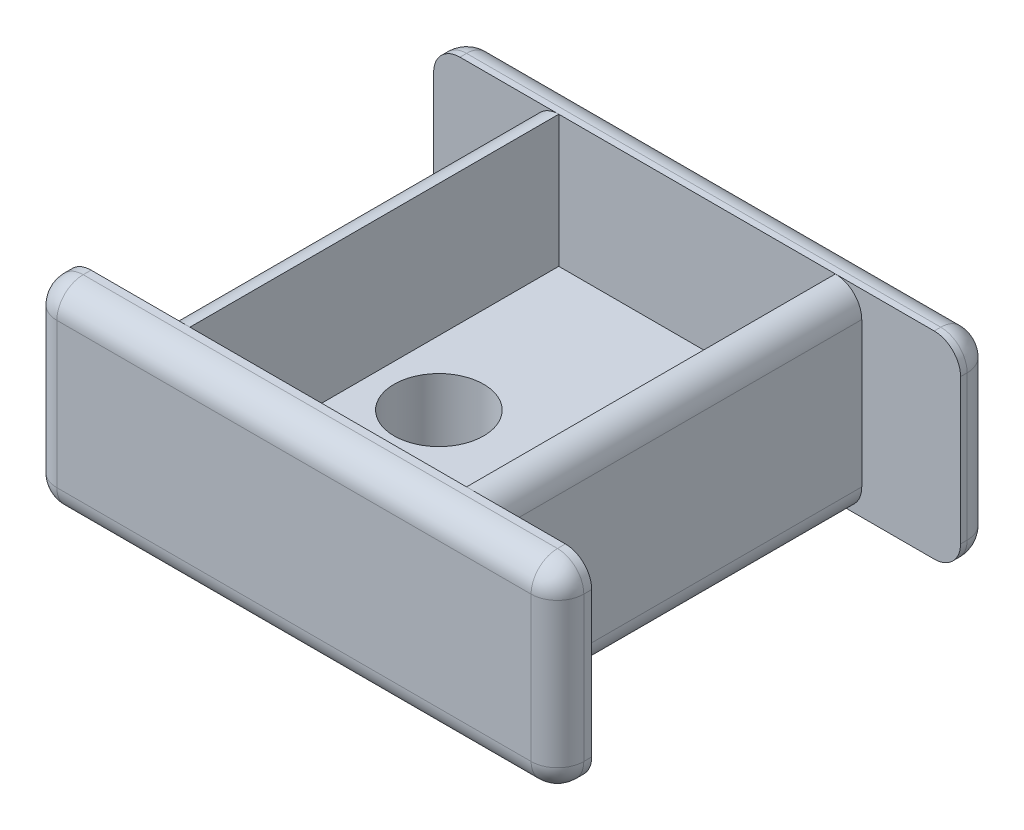
SolidWorks part; units mm, degrees
ref_plane "Front Plane" through (0, 0, 0) normal (0, 0, 1) x (1, 0, 0)
ref_plane "Top Plane" through (0, 0, 0) normal (0, 1, 0) x (1, 0, 0)
ref_plane "Right Plane" through (0, 0, 0) normal (1, 0, 0) x (0, 0, -1)
sketch "Sketch1" plane through (0, 0, 0) normal (0, 1, 0) x (1, 0, 0)
  line L0 (25.4, 20.955) -> (-25.4, 20.955)
  line L1 (-25.4, 20.955) -> (-25.4, 17.78)
  line L2 (25.4, 20.955) -> (25.4, 17.78)
  line L3 (25.4, 17.78) -> (15.875, 17.78)
  line L4 (15.875, 17.78) -> (15.875, -17.78)
  line L5 (15.875, -17.78) -> (25.4, -17.78)
  line L6 (25.4, -17.78) -> (25.4, -21.082)
  line L7 (25.4, -21.082) -> (-25.4, -21.082)
  line L8 (-25.4, -21.082) -> (-25.4, -17.78)
  line L9 (-25.4, -17.78) -> (-15.875, -17.78)
  line L10 (-15.875, -17.78) -> (-15.875, 17.78)
  line L11 (-15.875, 17.78) -> (-25.4, 17.78)
  line L12 (-15.875, 17.78) -> (15.875, -17.78) construction
  dimension "D1" = 50.8
  dimension "D2" = 35.56
  dimension "D3" = 3.302
  dimension "D4" = 3.175
  dimension "D5" = 31.75
extrude "Boss-Extrude1" add sketch "Sketch1" along normal blind 19.05
sketch "Sketch4" plane through (0, 19.05, 0) normal (0, 1, 0) x (1, 0, 0)
  circle A0 centre (6.985, 0) radius 4.064
  circle A1 centre (-7.112, 0) radius 4.318
  dimension "D2" = 8.636
  dimension "D4" = 6.985
  dimension "D3" = 7.112
extrude "Cut-Extrude3" cut sketch "Sketch4" against normal blind 38.1
fillet "Fillet8" radius 2.54 8 edges at (0, 0, -20.955) (-15.875, 0, 0) (15.875, 0, 0) (0, 0, 21.082) (15.875, 19.05, 0) (0, 19.05, -20.955) (-15.875, 19.05, 0) (0, 19.05, 21.082)
fillet "Fillet9" radius 2.54 20 edges at (-25.4, 9.525, 21.082) (-25.4, 18.3061, 20.3381) (-25.4, 9.525, -20.955) (-25.4, 18.3061, -20.2111) (25.4, 9.525, -20.955) (25.4, 18.3061, -20.2111) (25.4, 9.525, 21.082) (25.4, 18.3061, 20.3381) (-25.4, 19.05, 18.161) (-25.4, 19.05, -18.0975) (25.4, 19.05, -18.0975) (25.4, 19.05, 18.161) (-25.4, 0, 18.161) (-25.4, 0.7439, 20.3381) (-25.4, 0, -18.0975) (-25.4, 0.7439, -20.2111) (25.4, 0, -18.0975) (25.4, 0.7439, -20.2111) (25.4, 0, 18.161) (25.4, 0.7439, 20.3381)
sketch "Sketch9" plane through (0, 19.05, 0) normal (0, 1, 0) x (1, 0, 0)
  line L0 (-13.335, 17.78) -> (-13.335, -17.78) construction
  line L1 (-13.335, 17.78) -> (13.335, 17.78)
  line L2 (-13.335, 17.78) -> (-13.335, -17.78)
  line L3 (-13.335, -17.78) -> (13.335, -17.78)
  line L4 (13.335, 17.78) -> (13.335, -17.78)
  dimension "D1" = 35.56
extrude "Cut-Extrude6" cut sketch "Sketch9" against normal blind 12.7
sketch "Sketch10" plane through (-15.875, 0, 0) normal (-1, 0, 0) x (0, 0, 1)
  line L0 (-14.0836, 6.4731) -> (12.7717, 6.4731) construction
  text T0 "FUTURE" font "Engravers MT" height 3.5
extrude "Boss-Extrude2" add sketch "Sketch10" along normal blind 0.254
